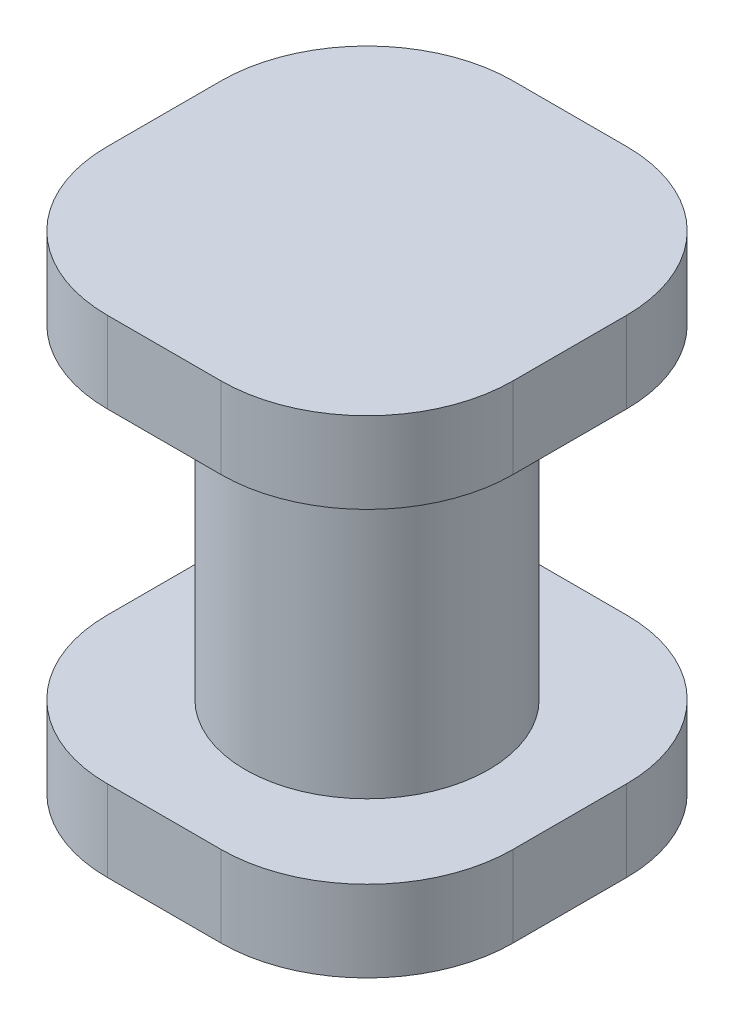
SolidWorks part; units mm, degrees
ref_plane "Front Plane" through (0, 0, 0) normal (0, 0, 1) x (1, 0, 0)
ref_plane "Top Plane" through (0, 0, 0) normal (0, 1, 0) x (1, 0, 0)
ref_plane "Right Plane" through (0, 0, 0) normal (1, 0, 0) x (0, 0, -1)
sketch "Sketch1" plane through (0, 0, 0) normal (0, 1, 0) x (1, 0, 0)
  circle A0 centre (0, 0) radius 7.5
  dimension "D1" = 15
extrude "Boss-Extrude1" add sketch "Sketch1" along normal blind 20
sketch "Sketch2" plane through (0, 20, 0) normal (0, 1, 0) x (1, 0, 0)
  line L0 (0, 0) -> (0, -12.5) construction
  line L1 (-3.5, -12.5) -> (3.5, -12.5)
  line L2 (-12.5, -3.5) -> (-12.5, 3.5)
  line L3 (-3.5, 12.5) -> (3.5, 12.5)
  line L4 (12.5, -3.5) -> (12.5, 3.5)
  line L5 (0, 0) -> (18.2986, 0) construction
  arc A1 (-12.5, -3.5) -> (-3.5, -12.5) centre (-3.5, -3.5) ccw
  arc A2 (3.5, -12.5) -> (12.5, -3.5) centre (3.5, -3.5) ccw
  arc A3 (12.5, 3.5) -> (3.5, 12.5) centre (3.5, 3.5) ccw
  arc A4 (-12.5, 3.5) -> (-3.5, 12.5) centre (-3.5, 3.5) cw
  point P8 (9.1493, 0)
  point P12 (-12.5, -12.5)
  point P17 (12.5, 12.5)
  point P20 (-12.5, 12.5)
  dimension "D1" = 25
  dimension "D6" = 9
  dimension "D2" = 25
  dimension "D3" = 12.5
  dimension "D4" = 12.5
  dimension "D5" = 12.5
extrude "Boss-Extrude2" add sketch "Sketch2" along normal blind 5
sketch "Sketch4" plane through (0, 0, 0) normal (0, -1, 0) x (1, 0, 0)
  line L0 (0, 0) -> (40.3541, 0) construction
  line L1 (-3.5, 12.5) -> (3.5, 12.5)
  line L2 (-12.5, 3.5) -> (-12.5, -3.5)
  line L3 (-3.5, -12.5) -> (3.5, -12.5)
  line L4 (12.5, 3.5) -> (12.5, -3.5)
  line L5 (0, 0) -> (0, 20.6354) construction
  arc A0 (-12.5, -3.5) -> (-3.5, -12.5) centre (-3.5, -3.5) ccw
  arc A1 (3.5, -12.5) -> (12.5, -3.5) centre (3.5, -3.5) ccw
  arc A2 (3.5, 12.5) -> (12.5, 3.5) centre (3.5, 3.5) cw
  arc A3 (-3.5, 12.5) -> (-12.5, 3.5) centre (-3.5, 3.5) ccw
  point P12 (12.5, -12.5)
  point P15 (12.5, 12.5)
  point P18 (-12.5, 12.5)
  dimension "D6" = 9
  dimension "D1" = 25
  dimension "D2" = 25
  dimension "D3" = 90
  dimension "D4" = 12.5
  dimension "D5" = 12.5
extrude "Boss-Extrude4" add sketch "Sketch4" along normal blind 5
scale "Scale1" scale about centroid uniform scaling yes scale factor 0.5
